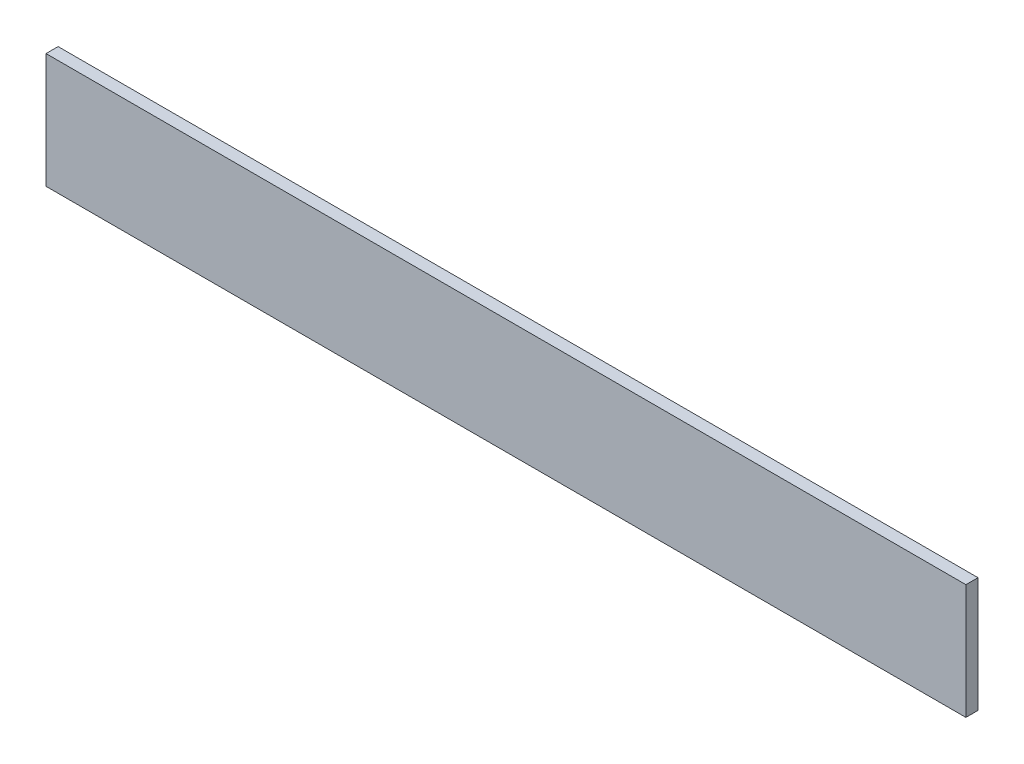
SolidWorks part; units mm, degrees
ref_plane "Plan de face" through (0, 0, 0) normal (0, 0, 1) x (1, 0, 0)
ref_plane "Plan de dessus" through (0, 0, 0) normal (0, 1, 0) x (1, 0, 0)
ref_plane "Plan de droite" through (0, 0, 0) normal (1, 0, 0) x (0, 0, -1)
sketch "Esquisse1" plane through (0, 0, 0) normal (0, 0, 1) x (1, 0, 0)
  line L1 (-142.6668, 70.5537) -> (237.3332, 70.5537)
  line L2 (-142.6668, 70.5537) -> (-142.6668, 23.0537)
  line L3 (-142.6668, 23.0537) -> (237.3332, 23.0537)
  line L4 (237.3332, 70.5537) -> (237.3332, 23.0537)
  dimension "D1" = 380
  dimension "D2" = 47.5
extrude "Boss.-Extru.1" add sketch "Esquisse1" along normal blind 5
